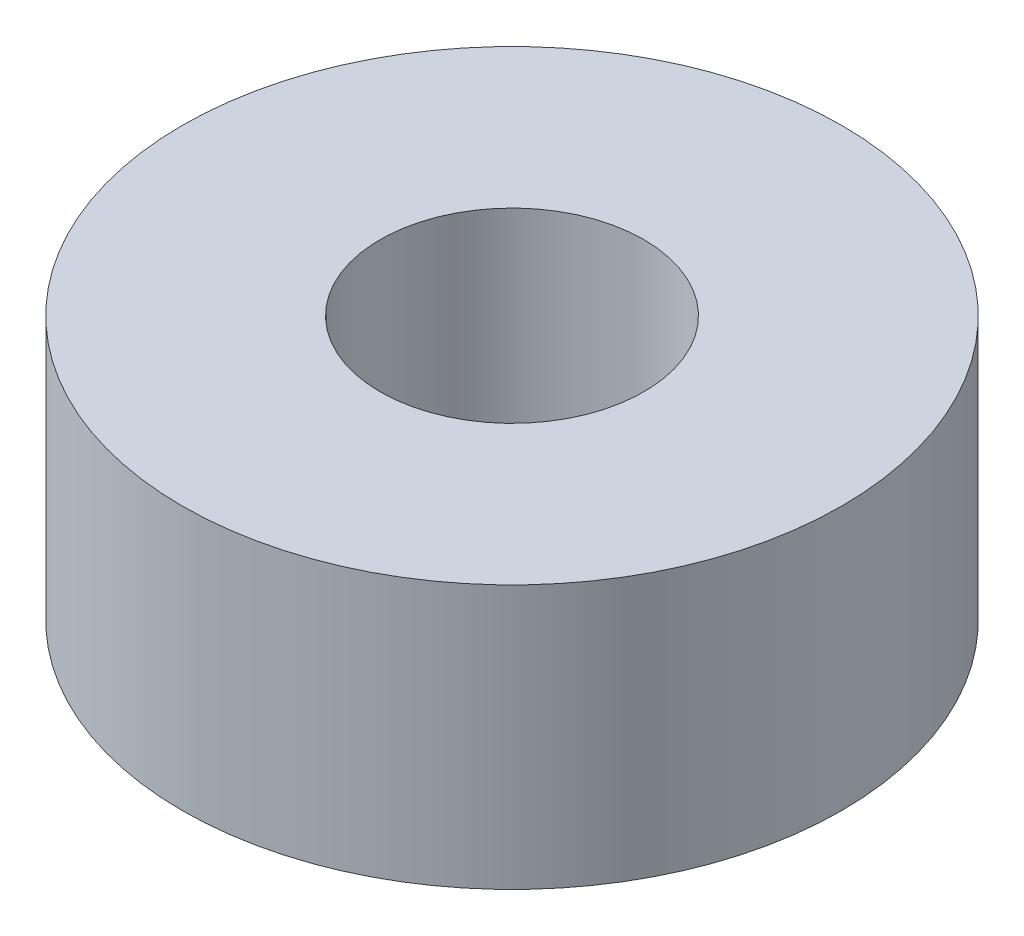
SolidWorks part; units mm, degrees
material "不锈钢 (铁素体)"
ref_plane "前视基准面" through (0, 0, 0) normal (0, 0, 1) x (1, 0, 0)
ref_plane "上视基准面" through (0, 0, 0) normal (0, 1, 0) x (1, 0, 0)
ref_plane "右视基准面" through (0, 0, 0) normal (1, 0, 0) x (0, 0, -1)
sketch "草图1" plane through (0, 0, 0) normal (0, 1, 0) x (1, 0, 0)
  circle A0 centre (0, 0) radius 2
  circle A1 centre (0, 0) radius 5
  dimension "D1" = 4
  dimension "D2" = 10
extrude "凸台-拉伸1" add sketch "草图1" along normal blind 4
